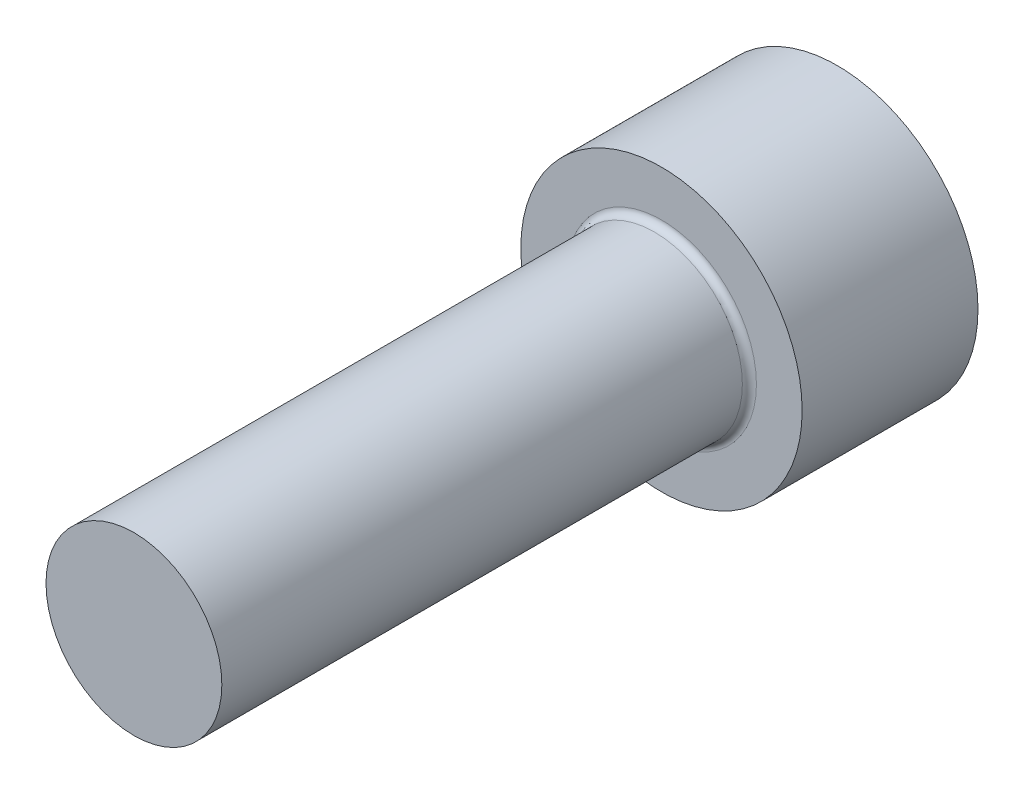
SolidWorks part; units mm, degrees
material "镀铬不锈钢"
ref_plane "前视基准面" through (0, 0, 0) normal (0, 0, 1) x (1, 0, 0)
ref_plane "上视基准面" through (0, 0, 0) normal (0, 1, 0) x (1, 0, 0)
ref_plane "右视基准面" through (0, 0, 0) normal (1, 0, 0) x (0, 0, -1)
sketch "草图1" plane through (0, 0, 0) normal (0, 0, 1) x (1, 0, 0)
  circle A0 centre (0, 0) radius 4
  dimension "头部直径" = 8
extrude "头部" add sketch "草图1" along normal blind 5
sketch "草图2" plane through (0, 0, 5) normal (0, 0, 1) x (1, 0, 0)
  circle A0 centre (0, 0) radius 2.5
  dimension "螺杆直径" = 5
extrude "螺杆" add sketch "草图2" along normal blind 15
fillet "圆角1" radius 0.2 1 edges at (2.5, 0, 5)
